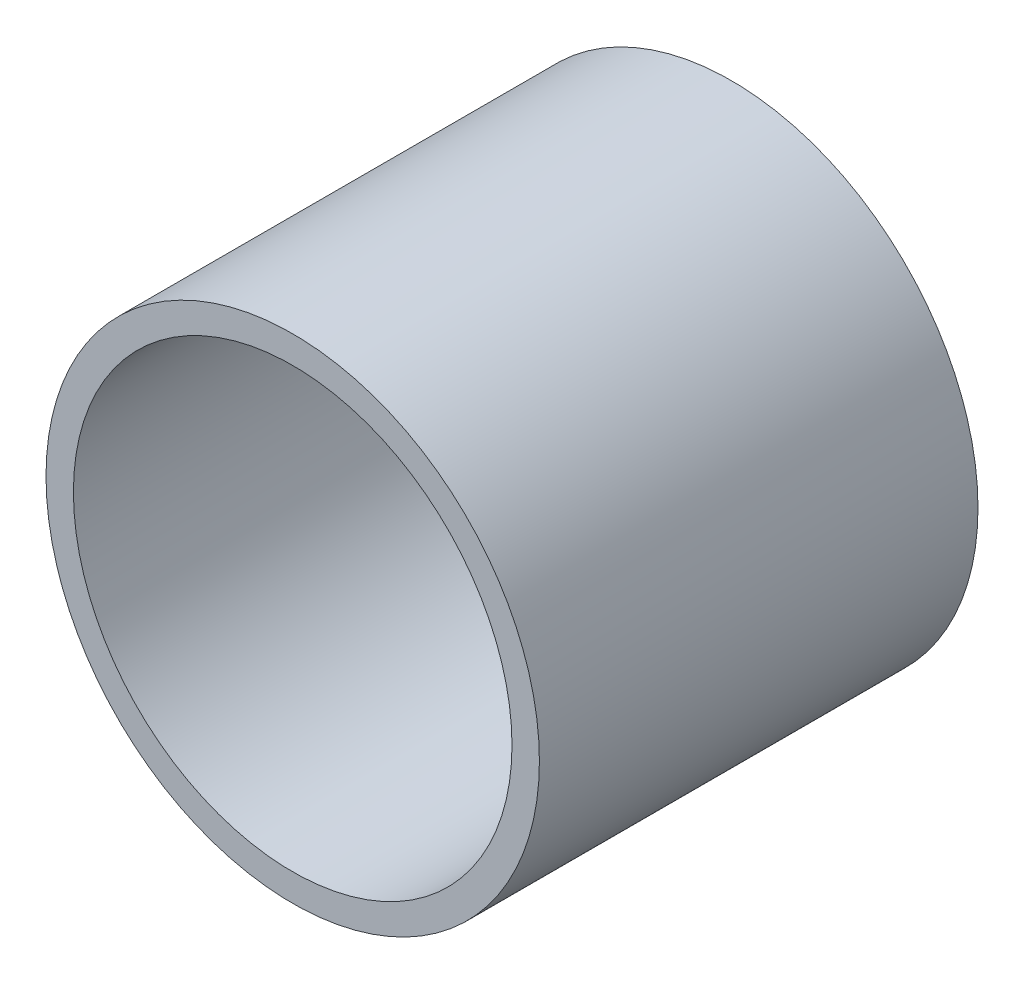
SolidWorks part; units mm, degrees
ref_plane "Front Plane" through (0, 0, 0) normal (0, 0, 1) x (1, 0, 0)
ref_plane "Top Plane" through (0, 0, 0) normal (0, 1, 0) x (1, 0, 0)
ref_plane "Right Plane" through (0, 0, 0) normal (1, 0, 0) x (0, 0, -1)
sketch "Sketch1" plane through (0, 0, 0) normal (0, 0, 1) x (1, 0, 0)
  circle A0 centre (0, 0) radius 4.5
  circle A1 centre (0, 0) radius 4
  dimension "D1" = 9
  dimension "D2" = 8
extrude "Boss-Extrude1" add sketch "Sketch1" along normal blind 8
